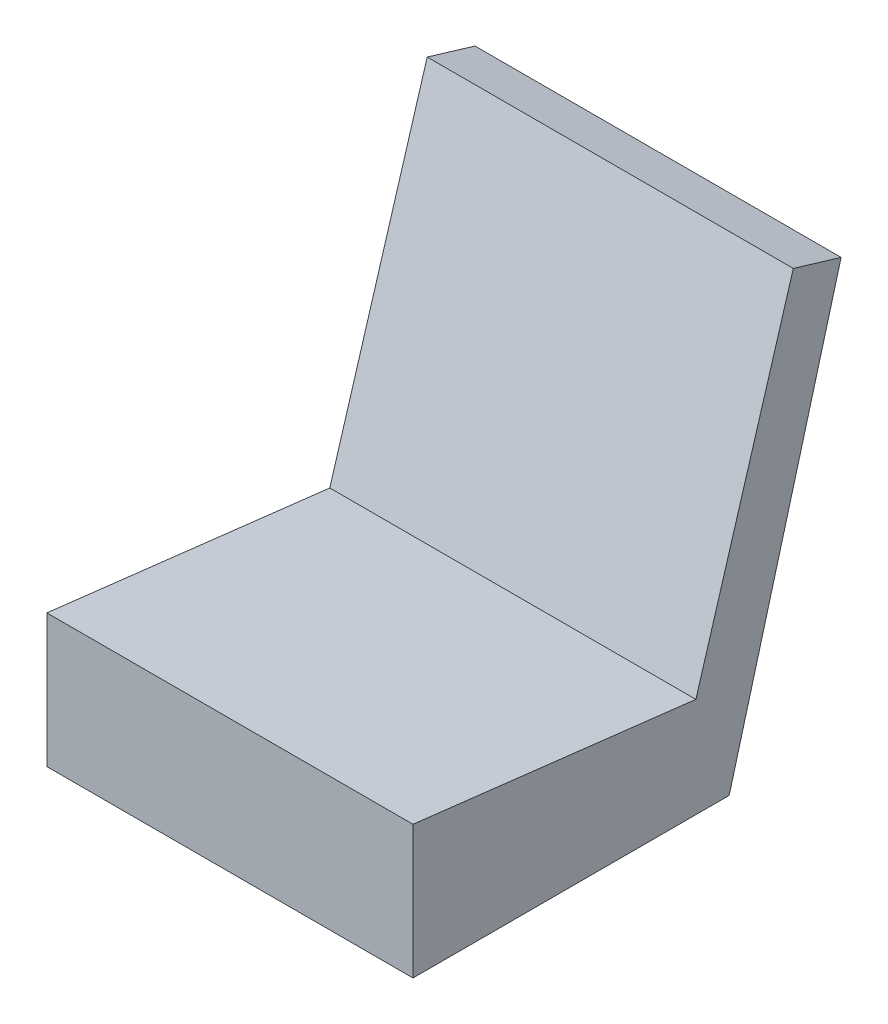
SolidWorks part; units mm, degrees
ref_plane "Front Plane" through (0, 0, 0) normal (0, 0, 1) x (1, 0, 0)
ref_plane "Top Plane" through (0, 0, 0) normal (0, 1, 0) x (1, 0, 0)
ref_plane "Right Plane" through (0, 0, 0) normal (1, 0, 0) x (0, 0, -1)
sketch "Sketch1" plane through (0, 0, 0) normal (1, 0, 0) x (0, 0, -1)
  line L0 (0, 0) -> (-482.6, 0)
  line L1 (-482.6, 0) -> (-482.6, 203.2)
  line L2 (-482.6, 203.2) -> (-50.8, 152.4)
  line L3 (-50.8, 152.4) -> (97.8898, 647.7)
  line L4 (97.8898, 647.7) -> (170.8721, 625.7906)
  line L5 (170.8721, 625.7906) -> (0, 0)
  dimension "D1" = 203.2
  dimension "D2" = 152.4
  dimension "D3" = 431.8
  dimension "D4" = 482.6
  dimension "D5" = 100
  dimension "D6" = 76.2
  dimension "D7" = 647.7
extrude "Boss-Extrude1" add sketch "Sketch1" along normal blind 558.8
